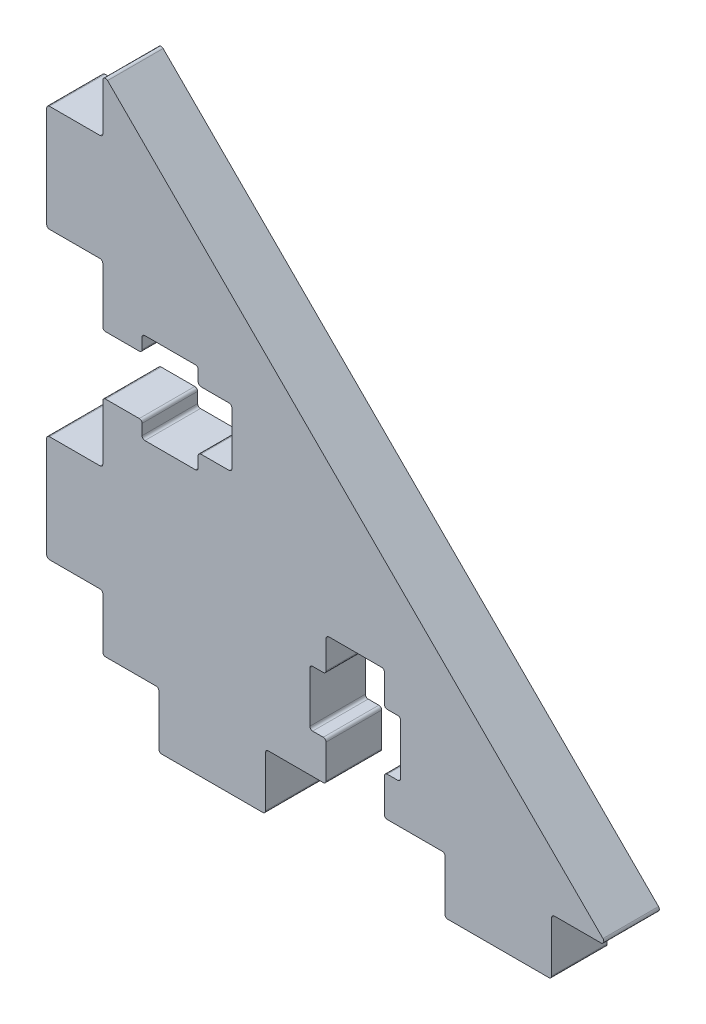
SolidWorks part; units mm, degrees
material "6061 Alloy"
ref_plane "Front Plane" through (0, 0, 0) normal (0, 0, 1) x (1, 0, 0)
ref_plane "Top Plane" through (0, 0, 0) normal (0, 1, 0) x (1, 0, 0)
ref_plane "Right Plane" through (0, 0, 0) normal (1, 0, 0) x (0, 0, -1)
sketch "Sketch2" plane through (0, 0, 0) normal (0, 0, 1) x (1, 0, 0)
  line L0 (0, 45) -> (0, 40)
  line L1 (0, 40) -> (-5, 40)
  line L2 (-5, 40) -> (-5, 30.5)
  line L3 (-5, 30.5) -> (0, 30.5)
  line L4 (0, 30.5) -> (0, 25.1)
  line L5 (0, 25.1) -> (3.5, 25.1)
  line L6 (3.5, 25.1) -> (3.5, 26.55)
  line L7 (3.5, 26.55) -> (8.5, 26.55)
  line L8 (8.5, 26.55) -> (8.5, 25.1)
  line L9 (8.5, 25.1) -> (11.5, 25.1)
  line L10 (11.5, 25.1) -> (11.5, 19.9)
  line L11 (11.5, 19.9) -> (8.5, 19.9)
  line L12 (8.5, 19.9) -> (8.5, 18.45)
  line L13 (8.5, 18.45) -> (3.5, 18.45)
  line L14 (3.5, 18.45) -> (3.5, 19.9)
  line L15 (3.5, 19.9) -> (0, 19.9)
  line L16 (0, 19.9) -> (0, 14.5)
  line L17 (0, 14.5) -> (-5, 14.5)
  line L18 (-5, 14.5) -> (-5, 5)
  line L19 (-5, 5) -> (0, 5)
  line L20 (0, 5) -> (0, 0)
  line L21 (0, 0) -> (22.5, 22.5) construction
  line L22 (0, 45) -> (45, 0)
  line L23 (19.9, 3.5) -> (19.785, 3.4577)
  line L24 (5, 0) -> (0, 0)
  line L25 (5, -5) -> (5, 0)
  line L26 (14.5, -5) -> (5, -5)
  line L27 (14.5, 0) -> (14.5, -5)
  line L28 (19.9, 0) -> (14.5, 0)
  line L29 (19.9, 3.5) -> (19.9, 0)
  line L30 (18.45, 3.5) -> (19.9, 3.5)
  line L31 (18.45, 8.5) -> (18.45, 3.5)
  line L32 (19.9, 8.5) -> (18.45, 8.5)
  line L33 (19.9, 11.5) -> (19.9, 8.5)
  line L34 (25.1, 11.5) -> (19.9, 11.5)
  line L35 (25.1, 8.5) -> (25.1, 11.5)
  line L36 (26.55, 8.5) -> (25.1, 8.5)
  line L37 (26.55, 3.5) -> (26.55, 8.5)
  line L38 (25.1, 3.5) -> (26.55, 3.5)
  line L39 (25.1, 0) -> (25.1, 3.5)
  line L40 (30.5, 0) -> (25.1, 0)
  line L41 (30.5, -5) -> (30.5, 0)
  line L42 (40, -5) -> (30.5, -5)
  line L43 (40, 0) -> (40, -5)
  line L44 (3.5, 19.9) -> (3.4577, 19.785)
  line L45 (45, 0) -> (40, 0)
  point P27 (22.5, 22.5)
  dimension "D1" = 45
  dimension "D2" = 8.1
  dimension "D3" = 45
  dimension "D4" = 5.2
  dimension "D5" = 3.5
  dimension "D6" = 5
  dimension "D7" = 9.5
  dimension "D8" = 5
  dimension "D9" = 5
  dimension "D10" = 3
extrude "Boss-Extrude1" add sketch "Sketch2" along normal blind 4.95
fillet "Fillet1" radius 0.25 15 edges at (45, 0, 2.475) (40, -5, 2.475) (30.5, -5, 2.475) (25.1, 0, 2.475) (19.9, 0, 2.475) (14.5, -5, 2.475) (5, -5, 2.475) (0, 0, 2.475) (-5, 5, 2.475) (-5, 14.5, 2.475) (0, 19.9, 2.475) (0, 25.1, 2.475) (-5, 30.5, 2.475) (-5, 40, 2.475) (0, 45, 2.475)
fillet "Fillet2" radius 0.25 28 edges at (40, 0, 2.475) (30.5, 0, 2.475) (25.1, 3.5, 2.475) (26.55, 3.5, 2.475) (26.55, 8.5, 2.475) (25.1, 8.5, 2.475) (25.1, 11.5, 2.475) (19.9, 11.5, 2.475) (19.9, 8.5, 2.475) (18.45, 8.5, 2.475) (18.45, 3.5, 2.475) (19.9, 3.5, 2.475) (14.5, 0, 2.475) (5, 0, 2.475) (0, 5, 2.475) (0, 14.5, 2.475) (3.5, 18.45, 2.475) (8.5, 18.45, 2.475) (8.5, 19.9, 2.475) (11.5, 19.9, 2.475) (11.5, 25.1, 2.475) (8.5, 26.55, 2.475) (3.5, 26.55, 2.475) (0, 30.5, 2.475) (0, 40, 2.475) (3.5, 19.9, 2.475) (3.5, 25.1, 2.475) (8.5, 25.1, 2.475)
ref_plane "Plane1" through (44.6464, 0, 0) normal (1, 0, 0) x (0, 0, -1)
ref_plane "Plane2" through (0, 44.6464, 0) normal (0, 1, 0) x (1, 0, 0)
